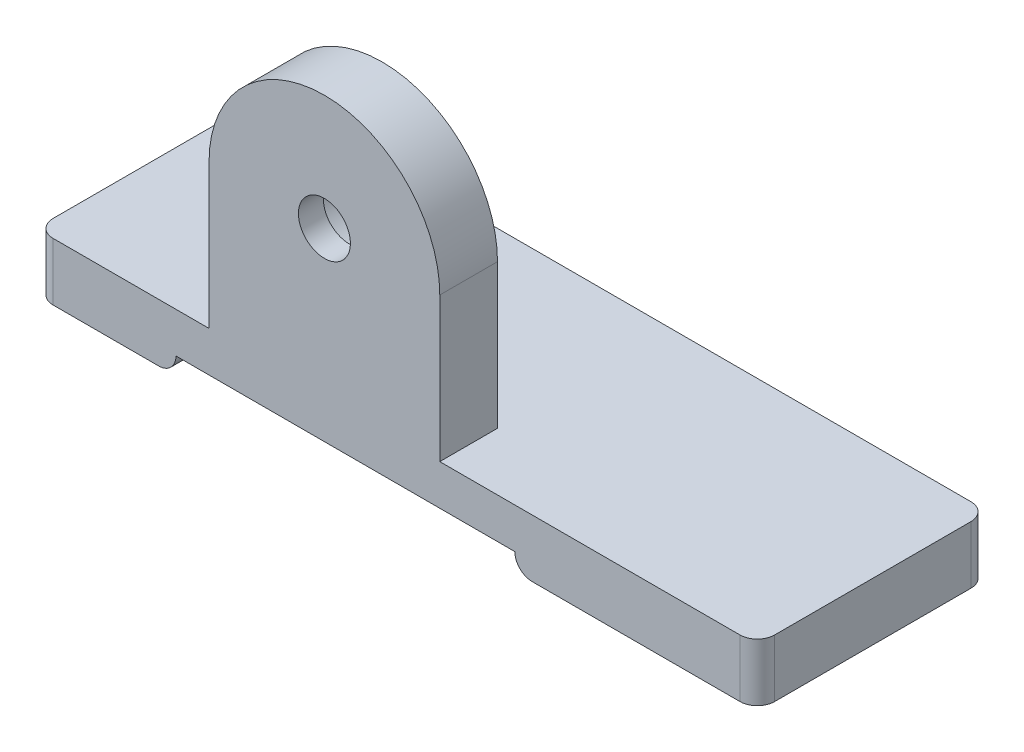
SolidWorks part; units mm, degrees
ref_plane "Front Plane" through (0, 0, 0) normal (0, 0, 1) x (1, 0, 0)
ref_plane "Top Plane" through (0, 0, 0) normal (0, 1, 0) x (1, 0, 0)
ref_plane "Right Plane" through (0, 0, 0) normal (1, 0, 0) x (0, 0, -1)
sketch "Sketch1" plane through (0, 0, 0) normal (0, 1, 0) x (1, 0, 0)
  line L1 (0, 0) -> (125, 0)
  line L2 (0, 0) -> (0, 40)
  line L3 (0, 40) -> (125, 40)
  line L4 (125, 0) -> (125, 40)
  dimension "D1" = 125
  dimension "D2" = 40
extrude "Boss-Extrude1" add sketch "Sketch1" along normal blind 10 contours L1 L4 L3 L2
sketch "Sketch4" plane through (0, 0, 0) normal (0, 0, 1) x (1, 0, 0)
  line L0 (0, 0) -> (125, 0) construction
  line L1 (30.0129, 0) -> (69.9871, 0)
  line L2 (30.0129, 0) -> (30.0129, 35)
  line L4 (69.9871, 0) -> (69.9871, 35)
  arc A2 (69.9871, 35) -> (30.0129, 35) centre (50, 35) ccw
  dimension "D2" = 35
extrude "Boss-Extrude2" add sketch "Sketch4" against normal blind 10 contours L4 A2 L2 L1
sketch "Sketch9" plane through (0, 0, 0) normal (0, 0, 1) x (1, 0, 0)
  line L0 (0, 0) -> (125, 0) construction
  line L1 (24.2826, 0) -> (82.9877, 0)
  line L2 (24.2826, 0) -> (24.2826, 3.0003)
  line L3 (24.2826, 3.0003) -> (82.9877, 3.0003)
  line L4 (82.9877, 0) -> (82.9877, 3.0003)
  point P6 (0, 0)
extrude "Cut-Extrude1" cut sketch "Sketch9" against normal blind 67
fillet "Fillet1" radius 3 4 edges at (0, 5, 0) (0, 5, -40) (125, 5, 0) (125, 5, -40)
fillet "Fillet2" radius 3 2 edges at (82.9877, 0, -20) (24.2826, 0, -20)
hole_wizard "CBORE for M8 Hex Head Bolt1" positions "3DSketch1" profile "Sketch10" counterbore size "M8" standard "ANSI Metric" end condition through all
sketch3d "3DSketch1"
  line L0 (50, 35, -10) -> (50, 35, 0) construction
  point P0 (50, 35, -10)
sketch "Sketch10" plane through (50, 35, -10) normal (1, 0, 0) x (0, 1, 0)
  line L0 (0, 0) -> (0, 10)
  line L1 (0, 10) -> (4.5, 10)
  line L3 (4.5, 10) -> (4.5, 5.68)
  line L4 (4.5, 5.68) -> (9.005, 5.68)
  line L5 (9.005, 5.68) -> (9.005, 0)
  line L7 (9.005, 0) -> (0, 0)
  line L11 (0, -6.35) -> (0, 107.95) construction
  dimension "Thru Hole Dia." = 9
  dimension "Thru Hole Depth" = 10
  dimension "C'Bore Dia." = 18.01
  dimension "C'Bore Depth" = 5.68
